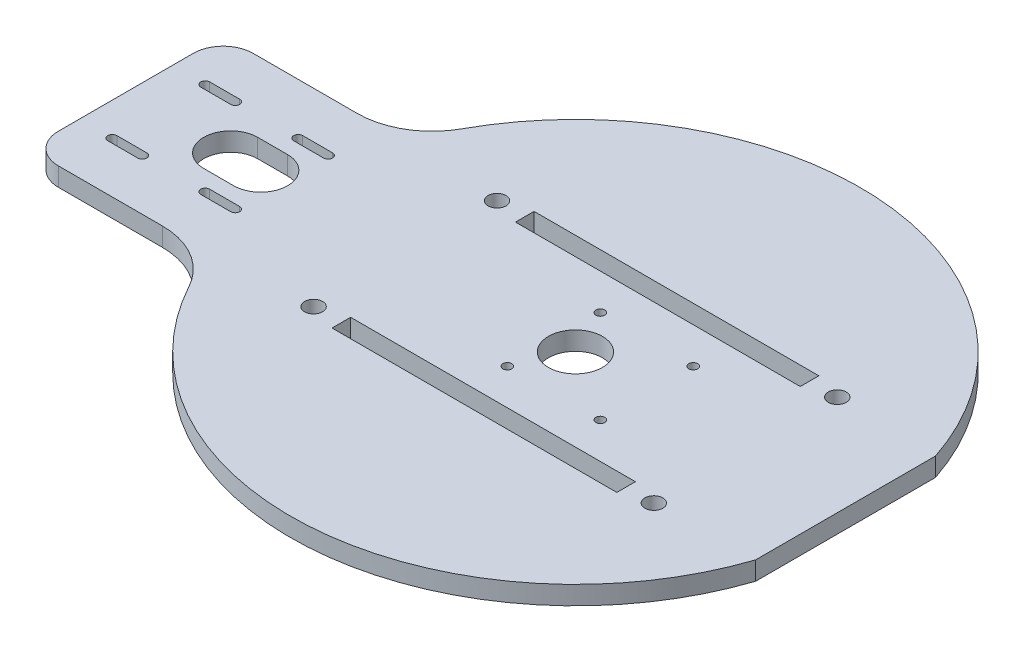
SolidWorks part; units mm, degrees
ref_plane "Front Plane" through (0, 0, 0) normal (0, 0, 1) x (1, 0, 0)
ref_plane "Top Plane" through (0, 0, 0) normal (0, 1, 0) x (1, 0, 0)
ref_plane "Right Plane" through (0, 0, 0) normal (1, 0, 0) x (0, 0, -1)
sketch "Sketch1" plane through (0, 0, 0) normal (0, 1, 0) x (1, 0, 0)
  line L0 (74.8154, 5.5955) -> (74.8154, -5.5955) construction
  line L1 (74.8154, -5.5955) -> (46.8543, -7.3426) construction
  line L2 (46.8543, 7.3426) -> (74.8154, 5.5955) construction
  line L22 (-150, 22.5) -> (-150, -22.5)
  line L27 (90.1388, -30) -> (90.1388, 30)
  line L31 (78.2287, 6.5992) -> (77.7924, 7.635) construction
  line L32 (77.7924, 7.635) -> (75.7862, 7.7655) construction
  line L33 (75.7862, 7.7655) -> (75.2194, 6.795) construction
  line L34 (75.2194, 6.795) -> (73.2133, 6.9256) construction
  line L35 (73.2133, 6.9256) -> (72.777, 7.9613) construction
  line L36 (72.777, 7.9613) -> (70.7709, 8.0918) construction
  line L37 (70.7709, 8.0918) -> (70.204, 7.1214) construction
  line L38 (70.204, 7.1214) -> (68.1979, 7.2519) construction
  line L39 (68.1979, 7.2519) -> (67.7616, 8.2876) construction
  line L40 (67.7616, 8.2876) -> (65.7555, 8.4182) construction
  line L41 (65.7555, 8.4182) -> (65.1887, 7.4477) construction
  line L42 (65.1887, 7.4477) -> (63.1825, 7.5782) construction
  line L43 (63.1825, 7.5782) -> (62.7462, 8.614) construction
  line L44 (62.7462, 8.614) -> (60.7401, 8.7445) construction
  line L45 (60.7401, 8.7445) -> (60.1733, 7.774) construction
  line L46 (60.1733, 7.774) -> (58.1671, 7.9046) construction
  line L47 (58.1671, 7.9046) -> (57.7308, 8.9403) construction
  line L48 (57.7308, 8.9403) -> (55.7247, 9.0708) construction
  line L49 (55.7247, 9.0708) -> (55.1579, 8.1004) construction
  line L50 (55.1579, 8.1004) -> (53.1517, 8.2309) construction
  line L51 (53.1517, 8.2309) -> (52.7155, 9.2666) construction
  line L52 (52.7155, 9.2666) -> (50.7093, 9.3972) construction
  line L53 (50.7093, 9.3972) -> (50.5352, 9.0991) construction
  line L54 (50.5352, 9.0991) -> (50.1425, 8.4267) construction
  line L55 (50.1425, 8.4267) -> (48.1363, 8.5572) construction
  line L56 (48.1363, 8.5572) -> (47.7001, 9.593) construction
  line L57 (47.7001, -9.593) -> (48.1363, -8.5572) construction
  line L58 (48.1363, -8.5572) -> (50.1425, -8.4267) construction
  line L59 (50.1425, -8.4267) -> (50.5352, -9.0991) construction
  line L60 (50.5352, -9.0991) -> (50.7093, -9.3972) construction
  line L61 (50.7093, -9.3972) -> (52.7155, -9.2666) construction
  line L62 (52.7155, -9.2666) -> (53.1517, -8.2309) construction
  line L63 (53.1517, -8.2309) -> (55.1579, -8.1004) construction
  line L64 (55.1579, -8.1004) -> (55.7247, -9.0708) construction
  line L65 (55.7247, -9.0708) -> (57.7308, -8.9403) construction
  line L66 (57.7308, -8.9403) -> (58.1671, -7.9046) construction
  line L67 (58.1671, -7.9046) -> (60.1733, -7.774) construction
  line L68 (60.1733, -7.774) -> (60.7401, -8.7445) construction
  line L69 (60.7401, -8.7445) -> (62.7462, -8.614) construction
  line L70 (62.7462, -8.614) -> (63.1825, -7.5782) construction
  line L71 (63.1825, -7.5782) -> (65.1887, -7.4477) construction
  line L72 (65.1887, -7.4477) -> (65.7555, -8.4182) construction
  line L73 (65.7555, -8.4182) -> (67.7616, -8.2876) construction
  line L74 (67.7616, -8.2876) -> (68.1979, -7.2519) construction
  line L75 (68.1979, -7.2519) -> (70.204, -7.1214) construction
  line L76 (70.204, -7.1214) -> (70.7709, -8.0918) construction
  line L77 (70.7709, -8.0918) -> (72.777, -7.9613) construction
  line L78 (72.777, -7.9613) -> (73.2133, -6.9256) construction
  line L79 (73.2133, -6.9256) -> (75.2194, -6.795) construction
  line L80 (75.2194, -6.795) -> (75.7862, -7.7655) construction
  line L81 (75.7862, -7.7655) -> (77.7924, -7.635) construction
  line L82 (77.7924, -7.635) -> (78.2287, -6.5992) construction
  line L83 (78.2287, -6.5992) -> (80.1965, -7.011) construction
  line L84 (80.1965, -7.011) -> (80.1585, -7.0267) construction
  line L85 (80.1585, -7.0267) -> (79.997, -8.1389) construction
  line L86 (79.997, -8.1389) -> (81.6473, -9.287) construction
  line L87 (81.6473, -9.287) -> (82.6339, -8.7489) construction
  line L88 (82.6339, -8.7489) -> (83.5261, -9.7764) construction
  line L89 (83.5261, 9.7764) -> (82.6339, 8.7489) construction
  line L90 (82.6339, 8.7489) -> (81.6473, 9.287) construction
  line L91 (81.6473, 9.287) -> (79.997, 8.1389) construction
  line L92 (79.997, 8.1389) -> (80.1585, 7.0267) construction
  line L93 (80.1585, 7.0267) -> (80.1965, 7.011) construction
  line L94 (80.1965, 7.011) -> (78.2287, 6.5992) construction
  line L95 (-140, -32.5) -> (-105.3269, -32.5)
  line L96 (-140, 32.5) -> (-105.3269, 32.5)
  line L97 (-150, 0) -> (0, 0) construction
  line L98 (-115, 0) -> (-105, 0) construction
  line L99 (-115, 9) -> (-105, 9)
  line L100 (-115, -9) -> (-105, -9)
  line L101 (-139, 15.5) -> (-129, 15.5) construction
  line L102 (-139, 17) -> (-129, 17)
  line L103 (-139, 14) -> (-129, 14)
  line L104 (-108, 15.5) -> (-98, 15.5) construction
  line L105 (-108, 17) -> (-98, 17)
  line L106 (-108, 14) -> (-98, 14)
  line L107 (-139, -15.5) -> (-129, -15.5) construction
  line L108 (-139, -14) -> (-129, -14)
  line L109 (-139, -17) -> (-129, -17)
  line L110 (-108, -15.5) -> (-98, -15.5) construction
  line L111 (-108, -14) -> (-98, -14)
  line L112 (-108, -17) -> (-98, -17)
  circle A0 centre (0, 0) radius 21.4693 construction
  circle A7 centre (0, 0) radius 9
  circle A8 centre (0, 0) radius 30.7694 construction
  arc A9 (46.8543, 7.3426) -> (46.8543, -7.3426) centre (47.308, 0) ccw construction
  arc A20 (-140, 32.5) -> (-150, 22.5) centre (-140, 22.5) ccw
  arc A21 (-150, -22.5) -> (-140, -32.5) centre (-140, -22.5) ccw
  arc A22 (-83.3838, -45.5208) -> (-105.3269, -32.5) centre (-105.3269, -57.5) ccw
  arc A23 (-83.3838, -45.5208) -> (90.1388, -30) centre (0, 0) ccw
  arc A24 (90.1388, 30) -> (-83.3838, 45.5208) centre (0, 0) ccw
  arc A25 (-105.3269, 32.5) -> (-83.3838, 45.5208) centre (-105.3269, 57.5) ccw
  arc A26 (47.7001, 9.593) -> (47.7001, -9.593) centre (47.4897, 0) ccw construction
  arc A27 (83.5261, 9.7764) -> (83.5261, -9.7764) centre (0, 0) ccw construction
  arc A28 (-115, 9) -> (-115, -9) centre (-115, 0) ccw
  arc A29 (-105, -9) -> (-105, 9) centre (-105, 0) ccw
  arc A30 (-139, 17) -> (-139, 14) centre (-139, 15.5) ccw
  arc A31 (-129, 14) -> (-129, 17) centre (-129, 15.5) ccw
  arc A32 (-108, 17) -> (-108, 14) centre (-108, 15.5) ccw
  arc A33 (-98, 14) -> (-98, 17) centre (-98, 15.5) ccw
  arc A34 (-139, -14) -> (-139, -17) centre (-139, -15.5) ccw
  arc A35 (-129, -17) -> (-129, -14) centre (-129, -15.5) ccw
  arc A36 (-108, -14) -> (-108, -17) centre (-108, -15.5) ccw
  arc A37 (-98, -17) -> (-98, -14) centre (-98, -15.5) ccw
  point P3 (-110, 0)
  point P12 (-134, 15.5)
  point P25 (-103, 15.5)
  point P33 (-134, -15.5)
  point P40 (-103, -15.5)
  dimension "D1" = 95
  dimension "D5" = 10
  dimension "D7" = 25
  dimension "D8" = 9
  dimension "D9" = 10
  dimension "D11" = 1.5
  dimension "D16" = 105
  dimension "D17" = 31
  dimension "D19" = 18
  dimension "D2" = 65
  dimension "D3" = 32.5
  dimension "D4" = 150
  dimension "D6" = 60
  dimension "D10" = 7
  dimension "D12" = 10
  dimension "D15" = 15.5
  dimension "D18" = 31
  dimension "D13" = 2
  dimension "D14" = 2
extrude "Boss-Extrude1" add sketch "Sketch1" against normal blind 6.2 contours A24 A25 A20 L22 A21 A22 A23 L27
sketch "Sketch2" plane through (0, -6.2, 0) normal (0, -1, 0) x (1, 0, 0)
  circle A0 centre (-7.2, 15.5) radius 1.5 construction
  circle A1 centre (-7.2, -15.5) radius 1.5 construction
  circle A2 centre (23.8, 15.5) radius 1.5 construction
  circle A3 centre (23.8, -15.5) radius 1.5 construction
  circle A4 centre (-7.2, 15.5) radius 1.5
  circle A5 centre (-7.2, -15.5) radius 1.5
  circle A6 centre (23.8, 15.5) radius 1.5
  circle A7 centre (23.8, -15.5) radius 1.5
extrude "Cut-Extrude1" cut sketch "Sketch2" against normal up to next
sketch "Sketch3" plane through (0, -6.2, 0) normal (0, -1, 0) x (1, 0, 0)
  line L1 (-56.75, -33.7) -> (-56.75, -27.5) construction
  circle A0 centre (-56.75, -30.6) radius 3
  circle A1 centre (56.75, -30.6) radius 3
  dimension "D1" = 6
  dimension "D3" = 113.5
  dimension "D2" = 2
sketch "Sketch4" plane through (0, -6.2, 0) normal (0, -1, 0) x (1, 0, 0)
  line L0 (-56.75, -33.7) -> (-56.75, -27.5) construction
  line L1 (-61.75, -33.7) -> (-51.75, -33.7) construction
  line L2 (-51.75, -27.5) -> (-61.75, -27.5) construction
extrude "Cut-Extrude2" cut sketch "Sketch3" against normal up to next contours A0 | A1
pattern_linear "LPattern1" count 2 spacing 61.2 along (0, 0, 1) of "Cut-Extrude2"
sketch "Sketch5" plane through (0, -6.2, 0) normal (0, -1, 0) x (1, 0, 0)
  line L0 (47.5, 33.7) -> (47.5, 27.5) construction
  line L1 (47.5, 33.7) -> (-47.5, 33.7) construction
  line L2 (-47.5, 33.7) -> (-47.5, 27.5) construction
  line L3 (47.5, 27.5) -> (-47.5, 27.5) construction
  line L4 (47.5, -33.7) -> (47.5, -27.5) construction
  line L5 (47.5, -27.5) -> (-47.5, -27.5) construction
  line L6 (-47.5, -33.7) -> (-47.5, -27.5) construction
  line L7 (47.5, -33.7) -> (-47.5, -33.7) construction
  line L8 (47.5, 33.7) -> (47.5, 27.5)
  line L9 (47.5, 33.7) -> (-47.5, 33.7)
  line L10 (-47.5, 33.7) -> (-47.5, 27.5)
  line L11 (47.5, 27.5) -> (-47.5, 27.5)
  line L12 (47.5, -33.7) -> (47.5, -27.5)
  line L13 (47.5, -27.5) -> (-47.5, -27.5)
  line L14 (-47.5, -33.7) -> (-47.5, -27.5)
  line L15 (47.5, -33.7) -> (-47.5, -33.7)
extrude "Cut-Extrude3" cut sketch "Sketch5" against normal up to next
